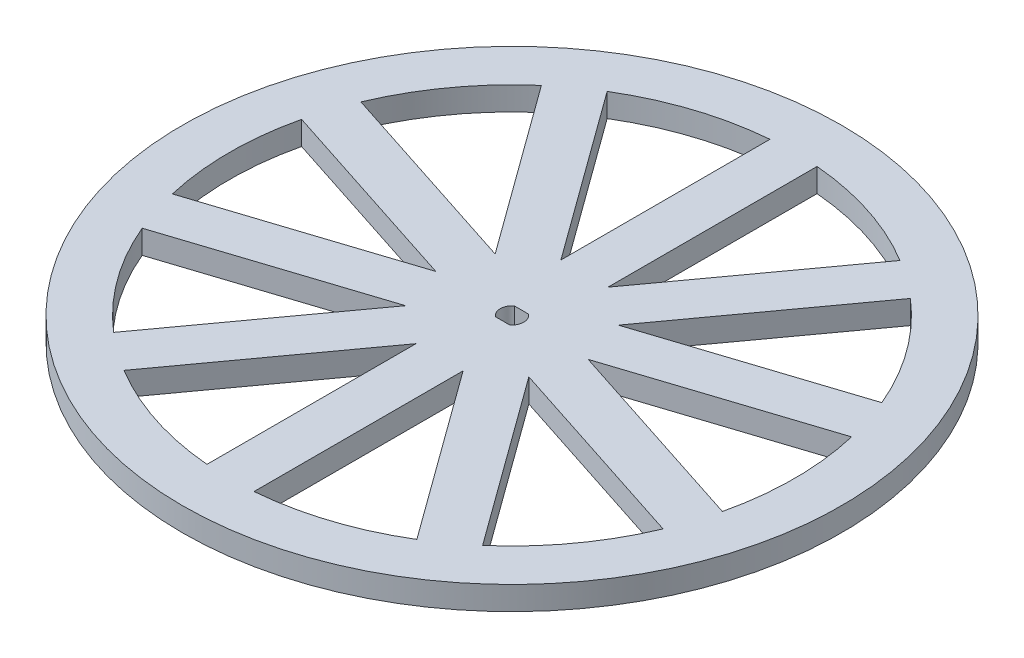
SolidWorks part; units mm, degrees
ref_plane "Front Plane" through (0, 0, 0) normal (0, 0, 1) x (1, 0, 0)
ref_plane "Top Plane" through (0, 0, 0) normal (0, 1, 0) x (1, 0, 0)
ref_plane "Right Plane" through (0, 0, 0) normal (1, 0, 0) x (0, 0, -1)
sketch "Sketch1" plane through (0, 0, 0) normal (0, 1, 0) x (1, 0, 0)
  line L0 (55.3198, 23.2318) -> (13.0902, 9.5106)
  line L5 (-5, 15.3884) -> (-31.0994, 51.3111)
  line L6 (5, 15.3884) -> (31.0994, 51.3111)
  line L8 (-5, 59.7913) -> (-5, 15.3884)
  line L10 (5, 59.7913) -> (5, 15.3884)
  line L13 (58.41, 13.7212) -> (16.1803, 0)
  line L16 (39.1895, -45.4333) -> (13.0902, -9.5106)
  line L17 (31.0994, -51.3111) -> (5, -15.3884)
  line L28 (-55.3198, 23.2318) -> (-13.0902, 9.5106)
  line L29 (-58.41, 13.7212) -> (-16.1803, 0)
  line L30 (-39.1895, -45.4333) -> (-13.0902, -9.5106)
  line L31 (-31.0994, -51.3111) -> (-5, -15.3884)
  line L35 (-13.0902, -9.5106) -> (-55.3198, -23.2318)
  line L36 (-5, -15.3884) -> (-5, -59.7913)
  line L45 (13.0902, -9.5106) -> (55.3198, -23.2318)
  line L46 (5, -15.3884) -> (5, -59.7913)
  line L49 (16.1803, 0) -> (58.41, -13.7212)
  line L50 (13.0902, 9.5106) -> (39.1895, 45.4333)
  line L59 (-13.0902, 9.5106) -> (-39.1895, 45.4333)
  line L60 (-16.1803, 0) -> (-58.41, -13.7212)
  line L74 (-1.5, -2) -> (1.5, -2)
  line L76 (-1.5, 2) -> (1.5, 2)
  line L77 (-71.9818, 28.6456) -> (-64.8588, 26.3312) [skipped]
  line L78 (-75.0719, 19.135) -> (-67.949, 16.8207) [skipped]
  line L82 (-49.4872, -59.6067) -> (-45.085, -53.5476) [skipped]
  line L83 (-41.397, -65.4846) -> (-36.9948, -59.4255) [skipped]
  arc A0 (1.5, -2) -> (1.5, 2) centre (0, 0) ccw
  circle A1 centre (0, 0) radius 70
  arc A2 (-58.41, 13.7212) -> (-58.41, -13.7212) centre (0, 0) ccw
  arc A3 (-1.5, 2) -> (-1.5, -2) centre (0, 0) ccw
  arc A4 (-31.0994, -51.3111) -> (-5, -59.7913) centre (0, 0) ccw
  arc A5 (-55.3198, -23.2318) -> (-39.1895, -45.4333) centre (0, 0) ccw
  arc A6 (-39.1895, 45.4333) -> (-55.3198, 23.2318) centre (0, 0) ccw
  arc A7 (-5, 59.7913) -> (-31.0994, 51.3111) centre (0, 0) ccw
  arc A8 (31.0994, 51.3111) -> (5, 59.7913) centre (0, 0) ccw
  arc A9 (55.3198, 23.2318) -> (39.1895, 45.4333) centre (0, 0) ccw
  arc A10 (58.41, -13.7212) -> (58.41, 13.7212) centre (0, 0) ccw
  arc A11 (5, -59.7913) -> (31.0994, -51.3111) centre (0, 0) ccw
  arc A12 (39.1895, -45.4333) -> (55.3198, -23.2318) centre (0, 0) ccw
  point P31 (0, 0)
  dimension "D1" = 5
extrude "Boss-Extrude1" add sketch "Sketch1" along normal blind 5
